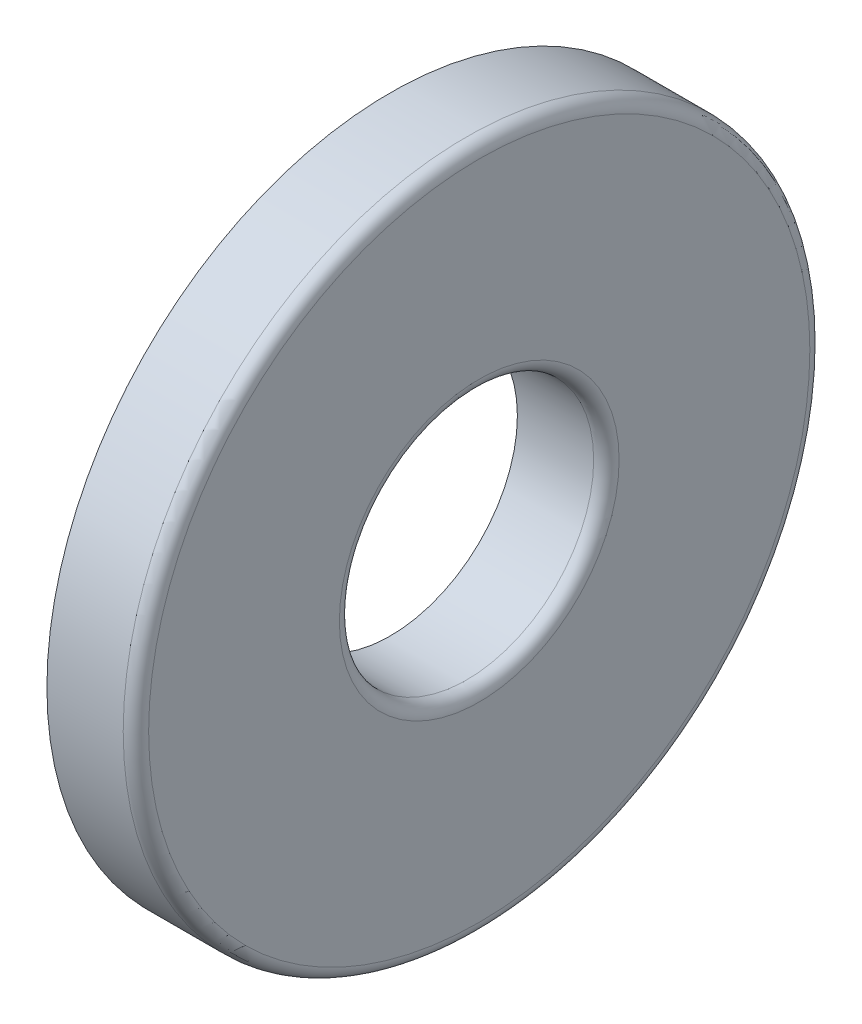
SolidWorks part; units mm, degrees
ref_plane "Plan1" through (0, 0, 0) normal (0, 0, 1) x (1, 0, 0)
ref_plane "Plan2" through (0, 0, 0) normal (0, 1, 0) x (1, 0, 0)
ref_plane "Plan3" through (0, 0, 0) normal (1, 0, 0) x (0, 0, -1)
sketch "Esquisse1" plane through (0, 0, 0) normal (0, 0, 1) x (1, 0, 0)
  line L0 (0, 0) -> (0, 7.3417)
  line L1 (0, 13.5) -> (3.5, 13.5)
  line L2 (3.5, 13.5) -> (3.5, 0)
  line L3 (-2.5, 0) -> (7, 0) construction
  line L4 (0, 10.6583) -> (0, 13.5)
  line L5 (0, 0) -> (3.5, 0)
  arc A0 (0, 7.3417) -> (0, 10.6583) centre (-2.5, 9) ccw
  dimension "D3" = 6
  dimension "D1" = 13.5
  dimension "D2" = 3.5
  dimension "D4" = 2.5
  dimension "D5" = 9
revolve "Base-Révolution" add sketch "Esquisse1" angle 360 about L3
fillet "Congé1" radius 0.5
sketch "Esquisse2" plane through (3.5, 0, 0) normal (1, 0, 0) x (0, 0, -1)
  circle A0 centre (0, 0) radius 5
  dimension "D1" = 10
extrude "Enlèv. mat.-Extru.1" cut sketch "Esquisse2" against normal through all
fillet "Congé2" radius 0.5
